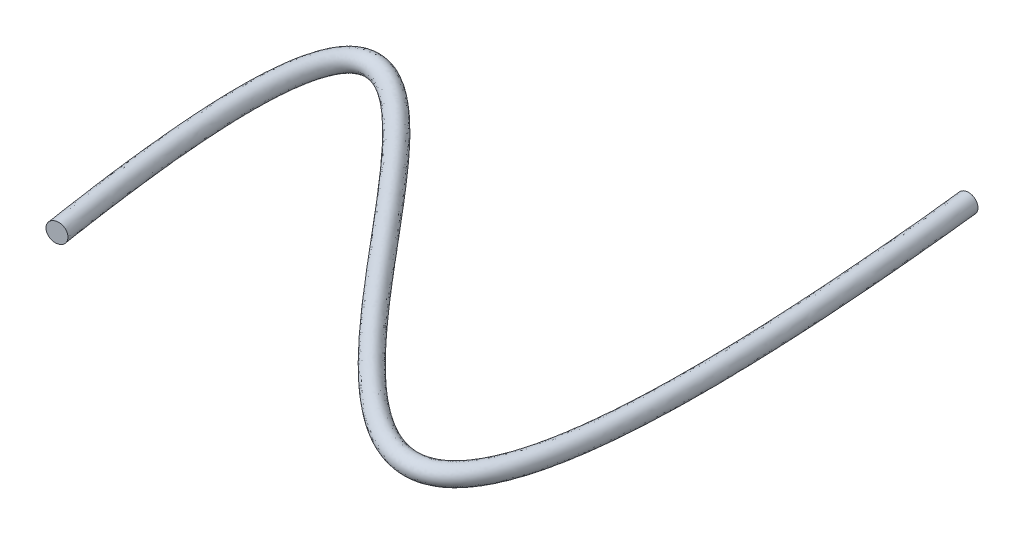
SolidWorks part; units mm, degrees
ref_plane "Front Plane" through (0, 0, 0) normal (0, 0, 1) x (1, 0, 0)
ref_plane "Top Plane" through (0, 0, 0) normal (0, 1, 0) x (1, 0, 0)
ref_plane "Right Plane" through (0, 0, 0) normal (1, 0, 0) x (0, 0, -1)
sketch "Sketch4" plane through (0, 0, 0) normal (0, 1, 0) x (1, 0, 0)
  spline S0 degree 3 poles (0, 0) (-25.486, 161.4785) (94.6239, -139.6061) (70.941, 79.4346) knots 0 0 0 0 1 1 1 1
ref_plane "Plane1" through (0, 0, 0) normal (0.1559, 0, 0.9878) x (0.9878, 0, -0.1559)
sketch "Sketch6" plane through (0, 0, 0) normal (0.1559, 0, 0.9878) x (0.9878, 0, -0.1559)
  circle A0 centre (0, 0) radius 1.5875
sweep "Sweep1" add profiles "Sketch6" path "Sketch4"
